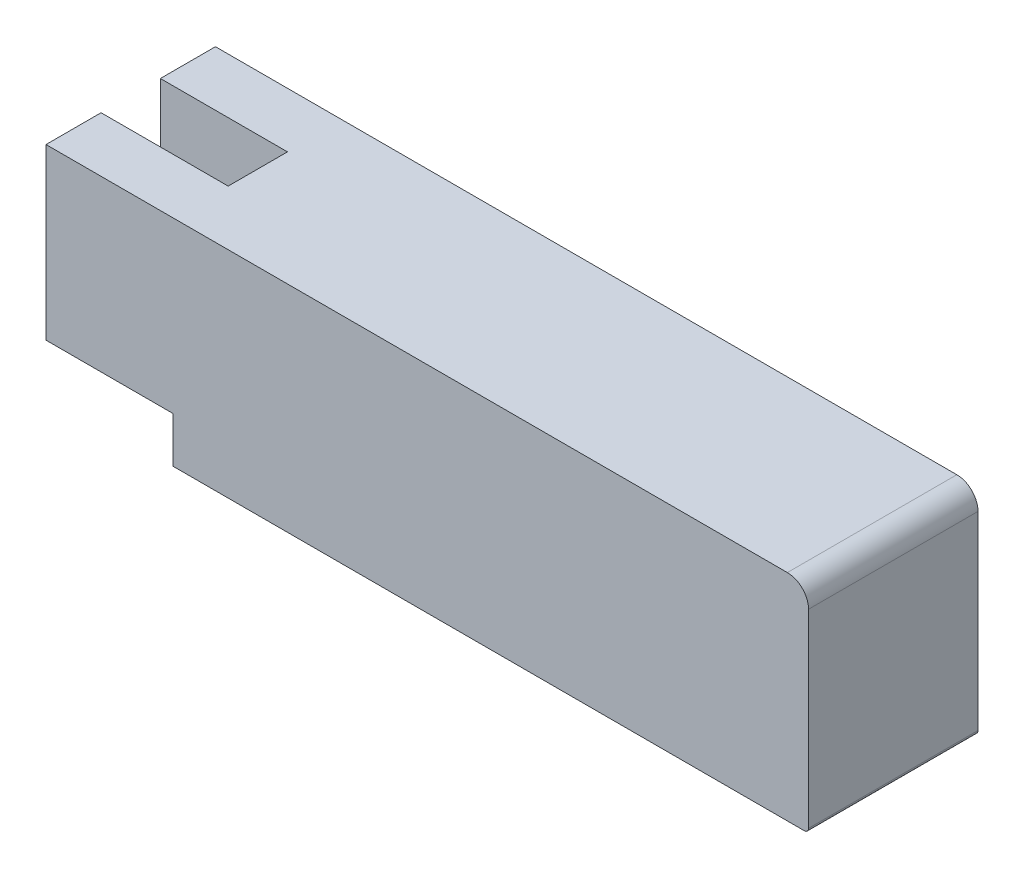
SolidWorks part; units mm, degrees
ref_plane "정면" through (0, 0, 0) normal (0, 0, 1) x (1, 0, 0)
ref_plane "윗면" through (0, 0, 0) normal (0, 1, 0) x (1, 0, 0)
ref_plane "우측면" through (0, 0, 0) normal (1, 0, 0) x (0, 0, -1)
sketch "스케치1" plane through (0, 0, 0) normal (0, 0, 1) x (1, 0, 0)
  line L0 (0, -40) -> (30, -40)
  line L1 (0, 0) -> (180, 0)
  line L2 (0, 0) -> (0, -40)
  line L3 (30, -50.78) -> (180, -50.78)
  line L4 (180, 0) -> (180, -50.78)
  line L5 (30, -40) -> (30, -50.78)
  dimension "D1" = 50.78
  dimension "D2" = 180
  dimension "D3" = 40
  dimension "D4" = 30
extrude "보스-돌출1" add sketch "스케치1" along normal mid plane 40 contours L1 L4 L3 L5 L0 L2
sketch "스케치2" plane through (0, 0, 0) normal (0, 0, 1) x (1, 0, 0)
  line L1 (0, 0) -> (30, 0)
  line L2 (0, 0) -> (0, -40)
  line L3 (0, -40) -> (30, -40)
  line L4 (30, 0) -> (30, -40)
extrude "컷-돌출1" cut sketch "스케치2" against normal mid plane 14
fillet "필렛1" radius 5 1 edges at (180, 0, 0)
fillet "필렛2" radius 1 1 edges at (180, -50.78, 0)
